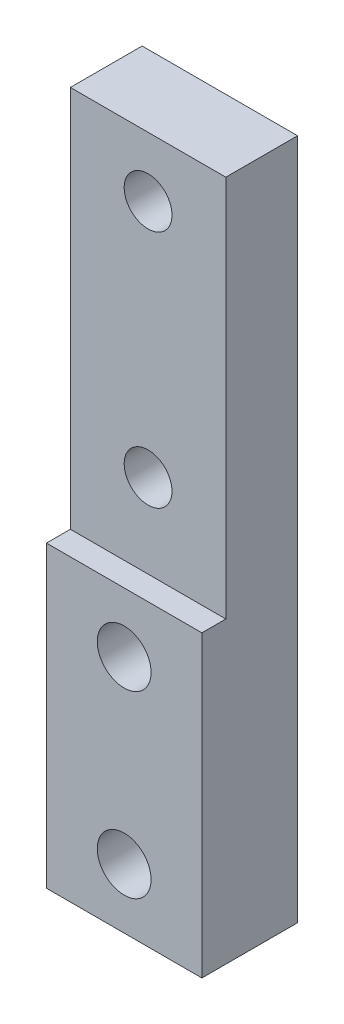
SolidWorks part; units mm, degrees
ref_plane "Front Plane" through (0, 0, 0) normal (0, 0, 1) x (1, 0, 0)
ref_plane "Top Plane" through (0, 0, 0) normal (0, 1, 0) x (1, 0, 0)
ref_plane "Right Plane" through (0, 0, 0) normal (1, 0, 0) x (0, 0, -1)
sketch "Sketch1" plane through (0, 0, 0) normal (0, 0, 1) x (1, 0, 0)
  line L0 (6.5, 0) -> (-6.5, 0) construction
  line L1 (-6.5, -12.5) -> (6.5, -12.5)
  line L2 (-6.5, -12.5) -> (-6.5, 12.5)
  line L3 (-6.5, 12.5) -> (6.5, 12.5)
  line L4 (6.5, -12.5) -> (6.5, 12.5)
  line L5 (-6.5, -12.5) -> (6.5, 12.5) construction
  line L6 (-6.5, 12.5) -> (6.5, -12.5) construction
  circle A0 centre (0, -7.5) radius 2
  circle A1 centre (0, 7.5) radius 2
  point P0 (0, 0)
  dimension "D3" = 4
  dimension "D4" = 7.5
  dimension "D1" = 13
  dimension "D2" = 25
extrude "Boss-Extrude1" add sketch "Sketch1" along normal blind 8
sketch "Sketch2" plane through (0, 0, 0) normal (0, 0, -1) x (-1, 0, 0)
  line L0 (-6.5, 12.5) -> (-6.5, 44.5)
  line L1 (6.5, 12.5) -> (6.5, 44.5)
  line L2 (6.5, 44.5) -> (-6.5, 44.5)
  line L3 (-6.5, 12.5) -> (6.5, 12.5)
  line L4 (0, 44.5) -> (0, 12.5) construction
  circle A0 centre (0, 39.5) radius 2
  circle A1 centre (0, 19.5) radius 2
  dimension "D2" = 4
  dimension "D3" = 4
  dimension "D5" = 20
  dimension "D1" = 32
  dimension "D4" = 5
extrude "Boss-Extrude2" add sketch "Sketch2" against normal blind 6
hole_wizard "CSK for M4 Countersunk Flat Head1" positions "Sketch3" profile "Sketch4" countersink size "M4" standard "BSI" end condition through all
sketch "Sketch3" plane through (0, 0, 0) normal (0, 0, -1) x (-1, 0, 0)
  point P0 (0, -7.5)
  point P3 (0, 7.5)
sketch "Sketch4" plane through (0, -7.5, 0) normal (1, 0, 0) x (0, 1, 0)
  line L0 (0, 0) -> (0, 8)
  line L1 (0, 8) -> (2.25, 8)
  line L2 (2.25, 8) -> (2.25, 2.45)
  line L3 (2.25, 2.45) -> (4.7, 0)
  line L5 (4.7, 0) -> (0, 0)
  line L6 (-2.25, 2.45) -> (-4.7, 0) construction
  line L11 (0, -6.35) -> (0, 107.95) construction
  dimension "Thru Hole Dia." = 4.5
  dimension "Thru Hole Depth" = 8
  dimension "Near C'Sink Dia." = 9.4
  dimension "Near C'Sink Angle" = 90
